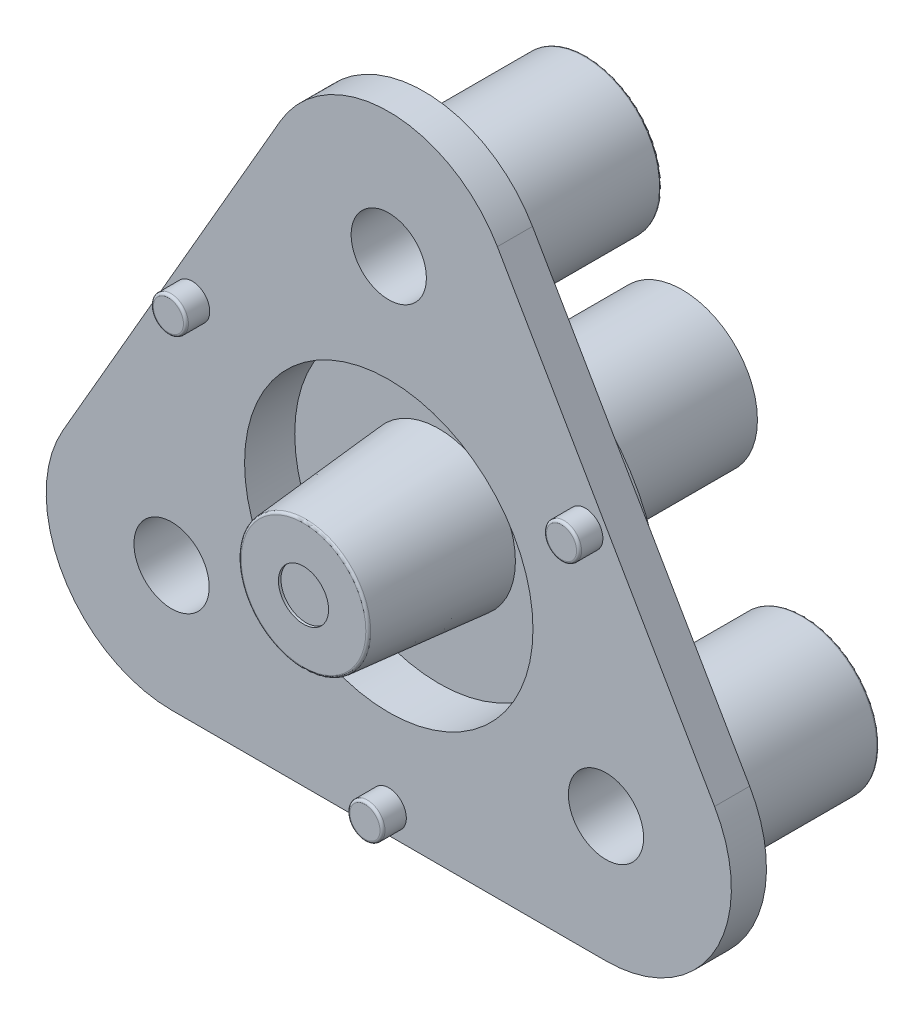
SolidWorks part; units mm, degrees
ref_plane "Front Plane" through (0, 0, 0) normal (0, 0, 1) x (1, 0, 0)
ref_plane "Top Plane" through (0, 0, 0) normal (0, 1, 0) x (1, 0, 0)
ref_plane "Right Plane" through (0, 0, 0) normal (1, 0, 0) x (0, 0, -1)
sketch "Sketch1" plane through (0, 0, 0) normal (0, 0, 1) x (1, 0, 0)
  line L1 (0, 20) -> (-17.3205, -10)
  line L2 (-17.3205, -10) -> (17.3205, -10)
  line L3 (17.3205, -10) -> (0, 20)
  line L4 (0, 10) -> (-8.6603, -5) construction
  line L5 (-8.6603, -5) -> (8.6603, -5) construction
  line L6 (8.6603, -5) -> (0, 10) construction
  circle A0 centre (0, 0) radius 10 construction
  circle A1 centre (0, 0) radius 10 construction
  circle A5 centre (0, 10) radius 5
  circle A6 centre (8.6603, -5) radius 5
  circle A7 centre (-8.6603, -5) radius 5
  point P1 (0, 10)
  dimension "D1" = 10
extrude "Boss-Extrude1" add sketch "Sketch1" along normal mid plane 1.4
sketch "Sketch2" plane through (0, 0, -0.7) normal (0, 0, -1) x (-1, 0, 0)
  circle A0 centre (0, 10) radius 3
  circle A1 centre (8.6603, -5) radius 3
  circle A2 centre (-8.6603, -5) radius 3
  arc A3 (4.3301, 12.5) -> (-4.3301, 12.5) centre (0, 10) ccw construction
  arc A4 (8.6603, -10) -> (12.9904, -2.5) centre (8.6603, -5) ccw construction
  arc A5 (-12.9904, -2.5) -> (-8.6603, -10) centre (-8.6603, -5) ccw construction
  dimension "D1" = 6
extrude "Boss-Extrude2" add sketch "Sketch2" along normal blind 6.5
sketch "Sketch3" plane through (0, 0, -0.7) normal (0, 0, -1) x (-1, 0, 0)
  circle A0 centre (0, 0) radius 7.4
  dimension "D1" = 14.8
extrude "Boss-Extrude3" add sketch "Sketch3" along normal blind 2
sketch "Sketch4" plane through (0, 0, -2.7) normal (0, 0, -1) x (-1, 0, 0)
  circle A0 centre (0, 0) radius 3
  dimension "D1" = 6
extrude "Boss-Extrude4" add sketch "Sketch4" along normal blind 8.3
sketch "Sketch6" plane through (0, 0, 0.7) normal (0, 0, 1) x (1, 0, 0)
  circle A0 centre (8.6603, -5) radius 1.5
  circle A1 centre (-8.6603, -5) radius 1.5
  circle A2 centre (0, 10) radius 1.5
  arc A3 (8.6603, -10) -> (12.9904, -2.5) centre (8.6603, -5) ccw construction
  arc A5 (4.3301, 12.5) -> (-4.3301, 12.5) centre (0, 10) ccw construction
  arc A6 (-12.9904, -2.5) -> (-8.6603, -10) centre (-8.6603, -5) ccw construction
  dimension "D1" = 3
extrude "Cut-Extrude2" cut sketch "Sketch6" against normal blind 6.4
sketch "Sketch8" plane through (0, 0, 0.7) normal (0, 0, 1) x (1, 0, 0)
  line L1 (0, -9.05) -> (7.8375, 4.525) construction
  line L2 (7.8375, 4.525) -> (-7.8375, 4.525) construction
  line L3 (-7.8375, 4.525) -> (0, -9.05) construction
  circle A0 centre (0, 0) radius 4.525 construction
  circle A1 centre (0, -9.05) radius 0.7
  circle A2 centre (7.8375, 4.525) radius 0.7
  circle A3 centre (-7.8375, 4.525) radius 0.7
  dimension "D2" = 1.4
  dimension "D1" = 9.05
extrude "Boss-Extrude5" add sketch "Sketch8" along normal blind 0.95
sketch "Sketch9" plane through (0, 0, 0.7) normal (0, 0, 1) x (1, 0, 0)
  circle A0 centre (0, 0) radius 5.75
  dimension "D1" = 11.5
extrude "Cut-Extrude3" cut sketch "Sketch9" against normal blind 2
sketch "Sketch10" plane through (0, 0, -1.3) normal (0, 0, 1) x (1, 0, 0)
  circle A0 centre (0, 0) radius 3.05
  dimension "D1" = 6.1
extrude "Boss-Extrude6" add sketch "Sketch10" along normal blind 5.4 draft 5
sketch "Sketch11" plane through (0, 0, 4.1) normal (0, 0, 1) x (1, 0, 0)
  circle A0 centre (0, 0) radius 1
  dimension "D1" = 2
extrude "Cut-Extrude4" cut sketch "Sketch11" against normal blind 0.1
sketch "Sketch5" plane through (0, 0, -11) normal (0, 0, -1) x (-1, 0, 0)
  circle A0 centre (0, 0) radius 1.5
  dimension "D1" = 3
extrude "Cut-Extrude1" cut sketch "Sketch5" against normal blind 14
fillet "Fillet1" radius 0.1 7 edges at (2.5776, 0, 4.1) (-11.6603, -5, -7.2) (-3, 10, -7.2) (5.6603, -5, -7.2) (8.5375, 4.525, 1.65) (0.7, -9.05, 1.65) (-7.1375, 4.525, 1.65)
sketch "Sketch13" plane through (0, 0, -11) normal (0, 0, -1) x (-1, 0, 0)
  line L0 (8.6603, -5) -> (0, 10) construction
  line L7 (0, 0) -> (-0.75, 1.299)
  line L8 (-0.75, 1.299) -> (-1.5, 0)
  line L9 (-1.5, 0) -> (-0.75, -1.299)
  line L10 (-0.75, -1.299) -> (0.75, -1.299)
  line L11 (0.75, -1.299) -> (1.5, 0)
  line L12 (1.5, 0) -> (0.75, 1.299)
  line L13 (0.75, 1.299) -> (-0.75, 1.299)
  circle A0 centre (0, 0) radius 1.5
  circle A1 centre (8.6603, -5) radius 2.9 construction
  circle A2 centre (0, 10) radius 2.9 construction
  circle A3 centre (0, 0) radius 1.5 construction
  circle M11 centre (0, 0) radius 1.5
extrude "Boss-Extrude7" add sketch "Sketch13" against normal up to surface (10.5 mm away) from offset 3.5 contours L9 M11 | L10 M11 | L11 M11 | L12 M11 | L13 M11 | L8 M11 up to face at (-1.5, 0, 3)
